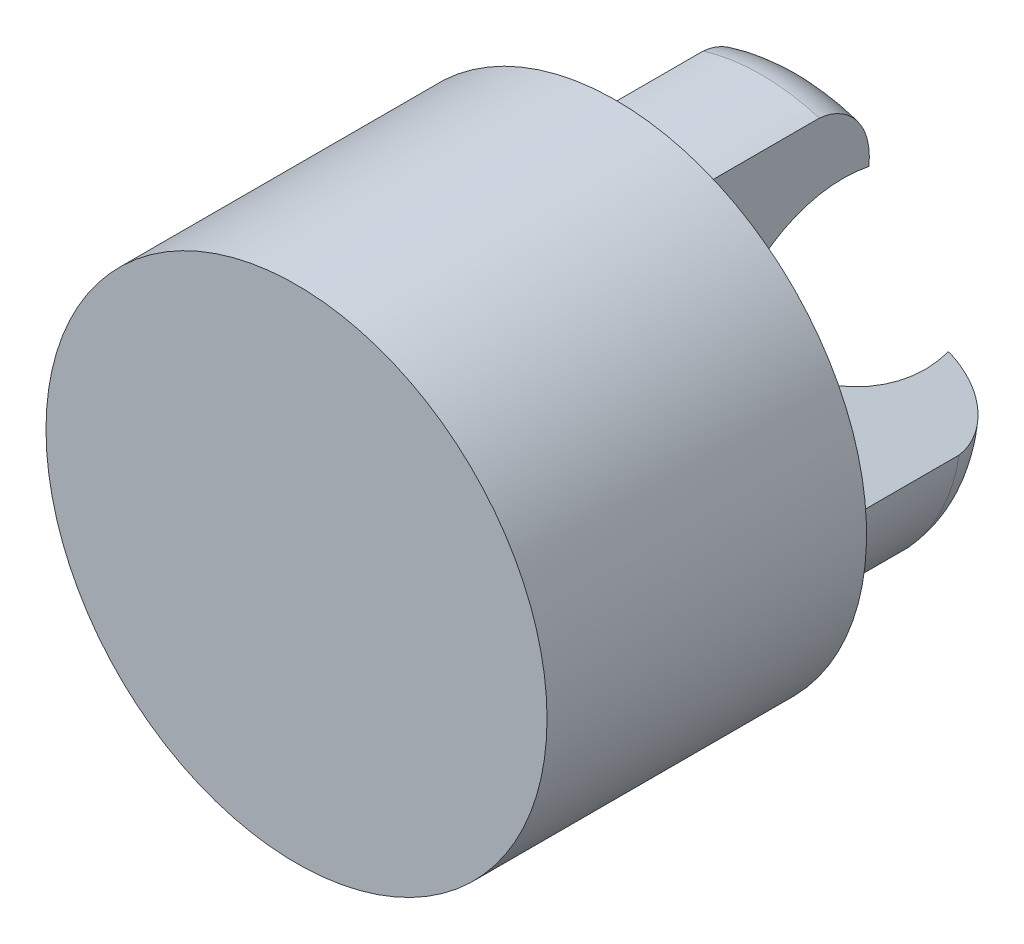
SolidWorks part; units mm, degrees
ref_plane "Plano frontal" through (0, 0, 0) normal (0, 0, 1) x (1, 0, 0)
ref_plane "Plano superior" through (0, 0, 0) normal (0, 1, 0) x (1, 0, 0)
ref_plane "Plano direito" through (0, 0, 0) normal (1, 0, 0) x (0, 0, -1)
sketch "Esboço1" plane through (0, 0, 0) normal (0, 1, 0) x (1, 0, 0)
  line L0 (0, 0) -> (6.8915, 0)
  line L1 (0, 0) -> (0, 19.1138) construction
  line L2 (6.8915, 5) -> (6.8915, 0)
  line L3 (0, 0.9958) -> (0, 0)
  arc A0 (0, 0.9958) -> (4.7436, 6.7035) centre (0, 5.8208) ccw
  arc A2 (6.8915, 5) -> (4.7436, 6.7035) centre (5, 4.8208) ccw
  dimension "D1" = 9.65
  dimension "D2" = 1
  dimension "D6" = 1.9
  dimension "D7" = 5
  dimension "D3" = 6.8915
  dimension "D4" = 5
revolve "Revolução1" add sketch "Esboço1" angle 360 about L1
sketch "Esboço3" plane through (0, 0, 0) normal (0, 0, 1) x (1, 0, 0)
  line L0 (-2, 19.3263) -> (-2, 1.7341)
  line L1 (-2, 1.7341) -> (-17.9373, -7.4673)
  line L2 (2, 19.3263) -> (2, 1.7341)
  line L3 (2, 1.7341) -> (17.9373, -7.4673)
  line L4 (0, -1.73) -> (-16.0273, -10.9833)
  line L5 (0, -1.73) -> (16.0273, -10.9833)
  arc A0 (-16.0273, -10.9833) -> (16.0273, -10.9833) centre (0, 0) ccw
  arc A1 (17.9373, -7.4673) -> (2, 19.3263) centre (0, 0) ccw
  arc A2 (-2, 19.3263) -> (-17.9373, -7.4673) centre (0, 0) ccw
  dimension "D8" = 38.8591
  dimension "D1" = 4
  dimension "D2" = 4
  dimension "D3" = 4
  dimension "D4" = 120
  dimension "D5" = 120
  dimension "D6" = 2
  dimension "D7" = 1.73
extrude "Corte-extrusão1" cut sketch "Esboço3" against normal through all
sketch "Esboço4" plane through (0, 0, 0) normal (0, 0, 1) x (1, 0, 0)
  arc A0 (-6.64, -7.4773) -> (6.64, -7.4773) centre (0, 0) ccw
  circle A1 centre (20, 0) radius 1.6
  circle A2 centre (-20, 0) radius 1.6
  arc A3 (-19.2842, 3.9354) -> (-19.2842, -3.9354) centre (-20, 0) ccw
  arc A4 (19.2842, -3.9354) -> (19.2842, 3.9354) centre (20, 0) ccw
  arc A5 (6.64, 7.4773) -> (19.2842, 3.9354) centre (16.6, 18.6933) ccw
  arc A6 (-19.2842, 3.9354) -> (-6.64, 7.4773) centre (-16.6, 18.6933) ccw
  arc A7 (-6.64, -7.4773) -> (-19.2842, -3.9354) centre (-16.6, -18.6933) ccw
  arc A8 (19.2842, -3.9354) -> (6.64, -7.4773) centre (16.6, -18.6933) ccw
  arc A9 (6.64, 7.4773) -> (-6.64, 7.4773) centre (0, 0) ccw
  dimension "D1" = 20
  dimension "D4" = 20
  dimension "D5" = 8
  dimension "D6" = 30
  dimension "D2" = 3.2
  dimension "D3" = 40
extrude "Ressalto-extrusão1" add sketch "Esboço4" along normal blind 4
sketch "Esboço5" plane through (0, 0, 0) normal (0, 0, -1) x (-1, 0, 0)
  line L1 (-27.4303, 14.6449) -> (29.9317, 14.6449)
  line L2 (-27.4303, 14.6449) -> (-27.4303, -14.5721)
  line L3 (-27.4303, -14.5721) -> (29.9317, -14.5721)
  line L4 (29.9317, 14.6449) -> (29.9317, -14.5721)
  circle A0 centre (0, 0) radius 10
extrude "Corte-extrusão2" cut sketch "Esboço5" against normal blind 10
sketch "Esboço6" plane through (0, 0, 0) normal (0, 0, -1) x (-1, 0, 0)
  circle A0 centre (0, 0) radius 8.625
  circle A1 centre (0, 0) radius 10
  dimension "D1" = 17.25
extrude "Corte-extrusão3" cut sketch "Esboço6" against normal blind 10
sketch "Esboço7" plane through (0, 0, 0) normal (1, 0, 0) x (0, 0, -1)
  line L0 (0, 0) -> (-4, 0) construction
  line L1 (-4, 8.625) -> (-4, -8.625) construction
sketch "Esboço8" plane through (0, 0, 4) normal (0, 0, 1) x (1, 0, 0)
  circle A0 centre (0, 0) radius 8.625
extrude "Ressalto-extrusão2" add sketch "Esboço8" along normal blind 7
